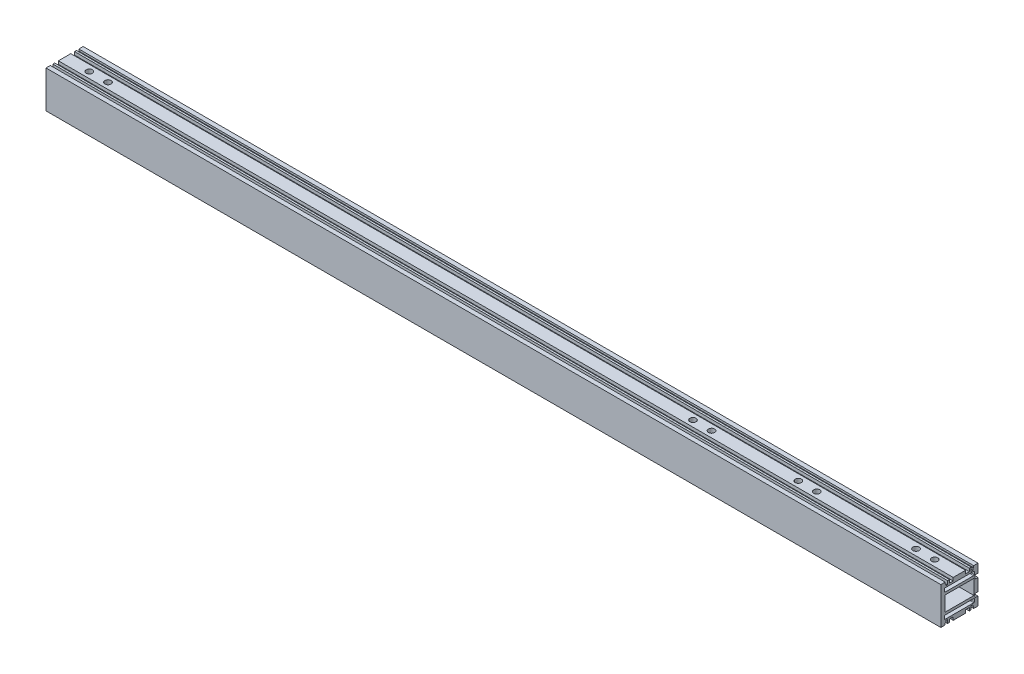
SolidWorks part; units mm, degrees
ref_plane "前视基准面" through (0, 0, 0) normal (0, 0, 1) x (1, 0, 0)
ref_plane "上视基准面" through (0, 0, 0) normal (0, 1, 0) x (1, 0, 0)
ref_plane "右视基准面" through (0, 0, 0) normal (1, 0, 0) x (0, 0, -1)
sketch "草图1" plane through (0, 0, 0) normal (1, 0, 0) x (0, 0, -1)
  line L0 (-15, 15) -> (15, -15) construction
  line L1 (-15, 15) -> (-11.5, 15)
  line L2 (-15, 15) -> (-15, -15)
  line L3 (-15, -15) -> (-11.5, -15)
  line L4 (15, 15) -> (15, 8)
  line L5 (15, 15) -> (-15, -15) construction
  line L6 (-11.5, 15) -> (-11.5, 13.5)
  line L7 (-11.5, 13.5) -> (-11, 13.5)
  line L8 (-11, 13.5) -> (-11, 12)
  line L9 (-11, 12) -> (-9.5, 12)
  line L10 (-9.5, 12) -> (-9.5, 15)
  line L11 (-9.5, 15) -> (-8, 15)
  line L12 (-8, 15) -> (-8, 12.5)
  line L13 (-8, 12.5) -> (-5, 12.5)
  line L14 (-5, 12.5) -> (-5, 15)
  line L15 (-5, 15) -> (5, 15)
  line L16 (0, 21.5201) -> (0, -18.309) construction
  line L17 (0, 55) -> (0, -55) construction
  line L18 (5, 12.5) -> (5, 15)
  line L19 (8, 12.5) -> (5, 12.5)
  line L20 (8, 15) -> (8, 12.5)
  line L21 (9.5, 15) -> (8, 15)
  line L22 (9.5, 12) -> (9.5, 15)
  line L23 (11, 12) -> (9.5, 12)
  line L24 (11, 13.5) -> (11, 12)
  line L25 (11.5, 13.5) -> (11, 13.5)
  line L26 (11.5, 15) -> (11.5, 13.5)
  line L27 (8, 15) -> (9.5, 15)
  line L28 (11.5, 15) -> (15, 15)
  line L29 (-19.8303, 0) -> (22.13, 0) construction
  line L30 (55, 0) -> (-55, 0) construction
  line L31 (8, -15) -> (9.5, -15)
  line L32 (11.5, -15) -> (11.5, -13.5)
  line L33 (11.5, -13.5) -> (11, -13.5)
  line L34 (11, -13.5) -> (11, -12)
  line L35 (11, -12) -> (9.5, -12)
  line L36 (9.5, -12) -> (9.5, -15)
  line L37 (9.5, -15) -> (8, -15)
  line L38 (8, -15) -> (8, -12.5)
  line L39 (8, -12.5) -> (5, -12.5)
  line L40 (5, -12.5) -> (5, -15)
  line L41 (-5, -15) -> (5, -15)
  line L42 (-5, -12.5) -> (-5, -15)
  line L43 (-8, -12.5) -> (-5, -12.5)
  line L44 (-8, -15) -> (-8, -12.5)
  line L45 (-9.5, -15) -> (-8, -15)
  line L46 (-9.5, -12) -> (-9.5, -15)
  line L47 (-11, -12) -> (-9.5, -12)
  line L48 (-11, -13.5) -> (-11, -12)
  line L49 (-11.5, -13.5) -> (-11, -13.5)
  line L50 (-11.5, -15) -> (-11.5, -13.5)
  line L51 (-9.5, -15) -> (-8, -15)
  line L52 (-5, -15) -> (5, -15)
  line L53 (8, -15) -> (9.5, -15)
  line L54 (11.5, -15) -> (15, -15)
  line L55 (15, 8) -> (12.5, 8)
  line L56 (12.5, 8) -> (12.5, 5)
  line L57 (12.5, 5) -> (15, 5)
  line L58 (12.5, -5) -> (15, -5)
  line L59 (12.5, -8) -> (12.5, -5)
  line L60 (15, -8) -> (12.5, -8)
  line L61 (15, 5) -> (15, -5)
  line L62 (15, -8) -> (15, -15)
  line L63 (12, -10.5) -> (12, -8.5)
  line L64 (-11.5, 11) -> (11.5, 11)
  line L65 (-12, 10.5) -> (-12, 8.5)
  line L66 (-11.5, 8) -> (11.5, 8)
  line L67 (12, 10.5) -> (12, 8.5)
  line L68 (-11.5, -8) -> (11.5, -8)
  line L69 (-12, -10.5) -> (-12, -8.5)
  line L70 (-11.5, -11) -> (11.5, -11)
  line L72 (-11.75, 6) -> (11.75, 6)
  line L73 (-11.75, 6) -> (-11.75, -6)
  line L74 (-11.75, -6) -> (11.75, -6)
  line L75 (11.75, 6) -> (11.75, -6)
  arc A0 (12, 8.5) -> (11.5, 8) centre (11.5, 8.5) cw
  arc A1 (11.5, 11) -> (12, 10.5) centre (11.5, 10.5) cw
  arc A2 (-11.5, 11) -> (-12, 10.5) centre (-11.5, 10.5) ccw
  arc A3 (-11.5, 8) -> (-12, 8.5) centre (-11.5, 8.5) cw
  arc A8 (-11.5, -8) -> (-12, -8.5) centre (-11.5, -8.5) ccw
  arc A9 (-11.5, -11) -> (-12, -10.5) centre (-11.5, -10.5) cw
  arc A10 (11.5, -11) -> (12, -10.5) centre (11.5, -10.5) ccw
  arc A11 (12, -8.5) -> (11.5, -8) centre (11.5, -8.5) ccw
  point P69 (12, 11)
  point P72 (-12, 11)
  point P77 (-11, -13.5)
  point P80 (11, -13.5)
  point P83 (11, 13.5)
  point P86 (-11, 13.5)
  point P99 (-12, -11)
  point P100 (12, -11)
  dimension "D17" = 0.5
  dimension "D1" = 3.5
  dimension "D2" = 1.5
  dimension "D3" = 0.5
  dimension "D4" = 1.5
  dimension "D5" = 3
  dimension "D6" = 30
  dimension "D7" = 30
  dimension "D8" = 1.5
  dimension "D9" = 2.5
  dimension "D10" = 3
  dimension "D11" = 2.5
  dimension "D12" = 7
  dimension "D13" = 3
  dimension "D14" = 4
  dimension "D15" = 3
  dimension "D16" = 24
  dimension "D19" = 23.5
  dimension "D20" = 12
extrude "凸台-拉伸1" add sketch "草图1" along normal mid plane 722
hole_wizard "M6 螺纹孔1" positions "草图3" profile "草图2" tap size "M6" standard "GB"
sketch "草图3" plane through (0, 15, 0) normal (0, 1, 0) x (1, 0, 0)
  point P0 (341, 0)
  point P3 (326, 0)
  point P6 (246, 0)
  point P9 (231, 0)
  point P12 (161, 0)
  point P15 (146, 0)
  point P18 (-326, 0)
  point P21 (-341, 0)
sketch "草图2" plane through (341, 15, 0) normal (1, 0, 0) x (0, 0, 1)
  line L0 (0, 0) -> (0, 20.5022)
  line L1 (0, 20.5022) -> (2.5, 19)
  line L2 (2.5, 19) -> (2.5, 0)
  line L5 (2.5, 0) -> (0, 0)
  line L10 (0, 20.5022) -> (-2.5, 19) construction
  line L11 (0, -6.35) -> (0, 107.95) construction
  dimension "螺纹孔钻头直径" = 5
  dimension "螺纹孔钻头深度" = 19
  dimension "导头角度" = 118
cosmetic thread "孔螺蚊线1" parameters "D1"=9, "D2"=6
cosmetic thread "孔螺蚊线2" parameters "D1"=9, "D2"=6
cosmetic thread "孔螺蚊线3" parameters "D1"=9, "D2"=6
cosmetic thread "孔螺蚊线4" parameters "D1"=9, "D2"=6
cosmetic thread "孔螺蚊线5" parameters "D1"=9, "D2"=6
cosmetic thread "孔螺蚊线6" parameters "D1"=9, "D2"=6
cosmetic thread "孔螺蚊线7" parameters "D1"=9, "D2"=6
cosmetic thread "孔螺蚊线8" parameters "D1"=9, "D2"=6
hole_wizard "M6 螺纹孔2" positions "草图5" profile "草图4" tap size "M6" standard "GB"
sketch "草图5" plane through (0, -15, 0) normal (0, -1, 0) x (-1, 0, 0)
  line L0 (-361, 15) -> (361, 15) construction
  line L1 (361, 11.5) -> (361, 15) construction
  point P0 (-128, 0)
  point P3 (-113, 0)
  point P6 (326, 0)
  point P9 (341, 0)
  point P12 (241, 0)
  point P14 (163, 0)
  dimension "D1" = 15
  dimension "D2" = 15
  dimension "D3" = 198
  dimension "D4" = 120
sketch "草图4" plane through (128, -15, 0) normal (1, 0, 0) x (0, 0, -1)
  line L0 (0, 0) -> (0, 20.5022)
  line L1 (0, 20.5022) -> (2.5, 19)
  line L2 (2.5, 19) -> (2.5, 0)
  line L5 (2.5, 0) -> (0, 0)
  line L10 (0, 20.5022) -> (-2.5, 19) construction
  line L11 (0, -6.35) -> (0, 107.95) construction
  dimension "螺纹孔钻头直径" = 5
  dimension "螺纹孔钻头深度" = 19
  dimension "导头角度" = 118
cosmetic thread "孔螺蚊线9" parameters "D1"=9, "D2"=6
cosmetic thread "孔螺蚊线10" parameters "D1"=9, "D2"=6
cosmetic thread "孔螺蚊线11" parameters "D1"=9, "D2"=6
cosmetic thread "孔螺蚊线12" parameters "D1"=9, "D2"=6
cosmetic thread "孔螺蚊线19" parameters "D1"=9, "D2"=6
cosmetic thread "孔螺蚊线20" parameters "D1"=9, "D2"=6
hole_wizard "M4 螺纹孔1" positions "草图7" profile "草图6" tap size "M4" standard "GB"
sketch "草图7" plane through (0, 0, -15) normal (0, 0, -1) x (-1, 0, 0)
  line L0 (-361, 15) -> (361, 15) construction
  line L1 (361, 5) -> (361, -5) construction
  point P0 (353, 0)
  point P2 (326, 0)
  dimension "D1" = 15
  dimension "D2" = 15
  dimension "D3" = 8
  dimension "D4" = 35
sketch "草图6" plane through (-353, 0, -15) normal (1, 0, 0) x (0, 1, 0)
  line L0 (0, 0) -> (0, 12.4914)
  line L1 (0, 12.4914) -> (1.65, 11.5)
  line L2 (1.65, 11.5) -> (1.65, 0)
  line L5 (1.65, 0) -> (0, 0)
  line L10 (0, 12.4914) -> (-1.65, 11.5) construction
  line L11 (0, -6.35) -> (0, 107.95) construction
  dimension "螺纹孔钻头直径" = 3.3
  dimension "螺纹孔钻头深度" = 11.5
  dimension "导头角度" = 118
cosmetic thread "孔螺蚊线13" parameters "D1"=3.25, "D2"=4
cosmetic thread "孔螺蚊线14" parameters "D1"=3.25, "D2"=4
hole_wizard "M6 螺纹孔4" positions "草图13" profile "草图12" tap size "M6" standard "GB"
sketch "草图13" plane through (0, 0, -15) normal (0, 0, -1) x (-1, 0, 0)
  line L0 (-361, 15) -> (361, 15) construction
  line L1 (-361, 5) -> (-361, -5) construction
  point P0 (-326, 0)
  point P2 (-341, 0)
  dimension "D1" = 15
  dimension "D2" = 15
  dimension "D3" = 20
  dimension "D4" = 35
sketch "草图12" plane through (326, 0, -15) normal (1, 0, 0) x (0, 1, 0)
  line L0 (0, 0) -> (0, 20.5022)
  line L1 (0, 20.5022) -> (2.5, 19)
  line L2 (2.5, 19) -> (2.5, 0)
  line L5 (2.5, 0) -> (0, 0)
  line L10 (0, 20.5022) -> (-2.5, 19) construction
  line L11 (0, -6.35) -> (0, 107.95) construction
  dimension "螺纹孔钻头直径" = 5
  dimension "螺纹孔钻头深度" = 19
  dimension "导头角度" = 118
cosmetic thread "孔螺蚊线21" parameters "D1"=3.25, "D2"=6
cosmetic thread "孔螺蚊线22" parameters "D1"=3.25, "D2"=6
